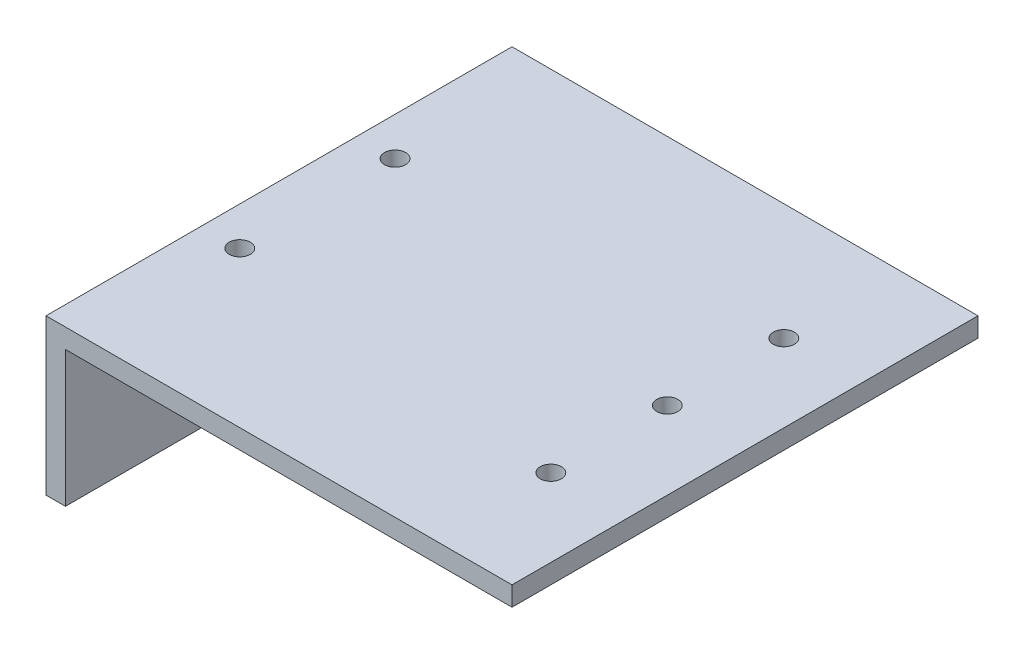
SolidWorks part; units mm, degrees
ref_plane "Front Plane" through (0, 0, 0) normal (0, 0, 1) x (1, 0, 0)
ref_plane "Top Plane" through (0, 0, 0) normal (0, 1, 0) x (1, 0, 0)
ref_plane "Right Plane" through (0, 0, 0) normal (1, 0, 0) x (0, 0, -1)
sketch "Sketch2" plane through (0, 0, 0) normal (0, 0, 1) x (1, 0, 0)
  line L0 (0, 0) -> (-76.2, 0)
  line L1 (-76.2, 0) -> (-76.2, -25.4)
  line L2 (-76.2, -25.4) -> (-73.025, -25.4)
  line L3 (-73.025, -25.4) -> (-73.025, -3.175)
  line L4 (-73.025, -3.175) -> (0, -3.175)
  line L5 (0, -3.175) -> (0, 0)
  dimension "D1" = 76.2
  dimension "D2" = 25.4
  dimension "D3" = 3.175
  dimension "D4" = 3.175
extrude "Boss-Extrude1" add sketch "Sketch2" along normal blind 76.2
hole_wizard "Tap Drill for #6-32 Tap1" positions "Sketch4" profile "Sketch3" hole size "#6-32" standard "ANSI Inch" end condition through all
sketch "Sketch4" plane through (-76.2, 0, 0) normal (-1, 0, 0) x (0, 0, 1)
  line L2 (76.2, 0) -> (0, 0) construction
  line L4 (12.7, 0) -> (12.7, -15.24) construction
  line L5 (12.7, -15.24) -> (25.4, -15.24) construction
  line L7 (76.2, 0) -> (25.4, 0) construction
  line L8 (25.4, 0) -> (25.4, -15.24) construction
  point P0 (25.4, -15.24)
  point P2 (12.7, -15.24)
  dimension "D1" = 15.24
  dimension "D2" = 12.7
  dimension "D3" = 12.7
sketch "Sketch3" plane through (-76.2, -15.24, 25.4) normal (0, 1, 0) x (0, 0, 1)
  line L0 (0, 0) -> (0, 76.2)
  line L1 (0, 76.2) -> (1.3525, 76.2)
  line L2 (1.3525, 76.2) -> (1.3525, 0)
  line L5 (1.3525, 0) -> (0, 0)
  line L11 (0, -6.35) -> (0, 107.95) construction
  dimension "Thru Hole Dia." = 2.7051
  dimension "Thru Hole Depth" = 76.2
hole_wizard "Tap Drill for #8-32 Tap1" positions "Sketch6" profile "Sketch5" hole size "#8-32" standard "ANSI Inch" end condition through all
sketch "Sketch6" plane through (0, 0, 0) normal (0, 1, 0) x (1, 0, 0)
  line L0 (-76.2, 0) -> (-69.9177, 0) construction
  line L1 (0, 0) -> (-76.2, 0) construction
  line L2 (0, -76.2) -> (-76.2, -76.2) construction
  point P0 (-69.9177, -25.4)
  point P2 (-69.9177, -50.8)
  dimension "D1" = 6.2823
  dimension "D2" = 25.4
  dimension "D3" = 25.4
sketch "Sketch5" plane through (-69.9177, 0, 25.4) normal (1, 0, 0) x (0, 0, 1)
  line L0 (0, 0) -> (0, 25.4)
  line L1 (0, 25.4) -> (1.7272, 25.4)
  line L2 (1.7272, 25.4) -> (1.7272, 0)
  line L5 (1.7272, 0) -> (0, 0)
  line L11 (0, -6.35) -> (0, 107.95) construction
  dimension "Thru Hole Dia." = 3.4544
  dimension "Thru Hole Depth" = 25.4
sketch "Sketch8" plane through (-76.2, 0, 0) normal (-1, 0, 0) x (0, 0, 1)
  line L1 (76.2, 0) -> (76.2, -25.4) construction
  line L2 (76.2, -15.24) -> (38.1, -15.24) construction
  line L3 (36.449, -16.891) -> (39.751, -16.891)
  line L4 (36.449, -16.891) -> (36.449, -13.589)
  line L5 (36.449, -13.589) -> (39.751, -13.589)
  line L6 (39.751, -16.891) -> (39.751, -13.589)
  line L7 (36.449, -16.891) -> (39.751, -13.589) construction
  line L8 (36.449, -13.589) -> (39.751, -16.891) construction
  dimension "D1" = 38.1
  dimension "D2" = 3.302
  dimension "D3" = 3.302
extrude "Cut-Extrude1" cut sketch "Sketch8" against normal up to next
hole_wizard "Tap Drill for #8-32 Tap2" positions "Sketch10" profile "Sketch9" hole size "#8-32" standard "ANSI Inch" end condition through all
sketch "Sketch10" plane through (0, 0, 0) normal (0, 1, 0) x (1, 0, 0)
  line L4 (0, -76.2) -> (0, 0) construction
  line L5 (0, 0) -> (-76.2, 0) construction
  point P0 (-12.7, -19.05)
  point P2 (-12.7, -38.1)
  point P4 (-12.7, -57.15)
  dimension "D1" = 19.05
  dimension "D2" = 19.05
  dimension "D3" = 12.7
  dimension "D4" = 19.05
sketch "Sketch9" plane through (-12.7, 0, 19.05) normal (1, 0, 0) x (0, 0, 1)
  line L0 (0, 0) -> (0, 25.4)
  line L1 (0, 25.4) -> (1.7272, 25.4)
  line L2 (1.7272, 25.4) -> (1.7272, 0)
  line L5 (1.7272, 0) -> (0, 0)
  line L11 (0, -6.35) -> (0, 107.95) construction
  dimension "Thru Hole Dia." = 3.4544
  dimension "Thru Hole Depth" = 25.4
